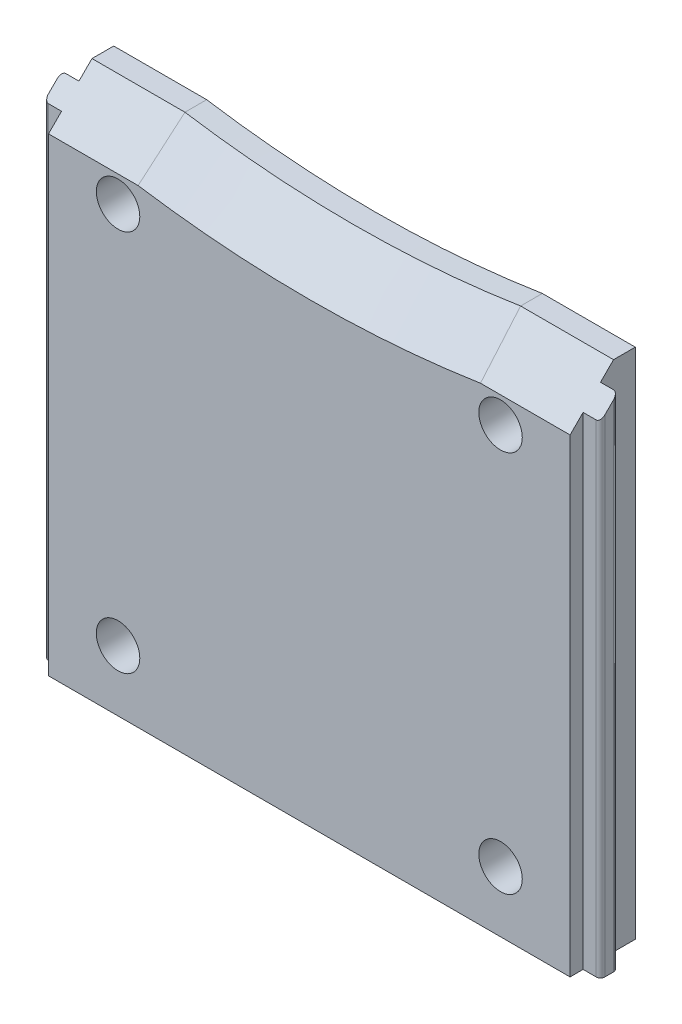
SolidWorks part; units mm, degrees
ref_plane "Front Plane" through (0, 0, 0) normal (0, 0, 1) x (1, 0, 0)
ref_plane "Top Plane" through (0, 0, 0) normal (0, 1, 0) x (1, 0, 0)
ref_plane "Right Plane" through (0, 0, 0) normal (1, 0, 0) x (0, 0, -1)
sketch "Sketch1" plane through (0, 0, 0) normal (0, 0, 1) x (1, 0, 0)
  line L0 (-15.24, 15.875) -> (-17.78, 15.875) construction
  line L1 (15.24, -15.875) -> (-15.24, -15.875)
  line L2 (15.24, -15.875) -> (15.24, 15.875) construction
  line L4 (-15.24, -15.875) -> (-15.24, 15.875) construction
  line L5 (15.24, -15.875) -> (-15.24, 15.875) construction
  line L6 (15.24, 15.875) -> (-15.24, -15.875) construction
  line L7 (15.24, 15.875) -> (17.78, 15.875) construction
  line L8 (-15.24, 15.1909) -> (-15.24, -15.875)
  line L9 (15.24, 15.1909) -> (15.24, -15.875)
  arc A1 (-17.78, 15.875) -> (17.78, 15.875) centre (0, 76.835) ccw construction
  arc A2 (-15.24, 15.1909) -> (15.24, 15.1909) centre (0, 76.835) ccw
  point P0 (0, 0)
  point P8 (0, 13.335)
  dimension "D2" = 2.54
  dimension "D1" = 31.75
  dimension "D3" = 2.54
  dimension "D4" = 30.48
extrude "Boss-Extrude1" add sketch "Sketch1" along normal blind 3.81
sketch "Sketch3" plane through (0, 0, 3.81) normal (0, 0, 1) x (1, 0, 0)
  line L1 (11.176, -12.319) -> (-11.176, -12.319) construction
  line L2 (11.176, -12.319) -> (11.176, 10.033) construction
  line L3 (11.176, 10.033) -> (-11.176, 10.033) construction
  line L4 (-11.176, -12.319) -> (-11.176, 10.033) construction
  line L5 (11.176, -12.319) -> (-11.176, 10.033) construction
  line L6 (11.176, 10.033) -> (-11.176, -12.319) construction
  circle A0 centre (-11.176, 10.033) radius 1.27
  circle A1 centre (11.176, 10.033) radius 1.27
  circle A2 centre (11.176, -12.319) radius 1.27
  circle A3 centre (-11.176, -12.319) radius 1.27
  point P0 (0, -1.143)
  dimension "D3" = 2.54
  dimension "D1" = 22.352
  dimension "D2" = 5.842
extrude "Cut-Extrude1" cut sketch "Sketch3" against normal blind 3.81
sketch "Sketch4" plane through (-15.24, 0, 0) normal (-1, 0, 0) x (0, 0, 1)
  line L0 (3.81, 15.1909) -> (0, 15.1909) construction
  line L1 (2.032, 15.1909) -> (3.048, 15.1909)
  line L2 (2.032, 15.1909) -> (2.032, -15.875)
  line L3 (2.032, -15.875) -> (3.048, -15.875)
  line L4 (3.048, 15.1909) -> (3.048, -15.875)
  line L5 (3.81, -15.875) -> (0, -15.875) construction
  line L6 (3.81, 15.1909) -> (3.81, -15.875) construction
  dimension "D1" = 1.016
  dimension "D2" = 0.762
extrude "Boss-Extrude3" add sketch "Sketch4" along normal blind 1.016
fillet "Fillet2" radius 0.254 2 edges at (-16.256, -0.342, 3.048) (-16.256, -0.342, 2.032)
mirror "Mirror4" about plane through (0, 0, 0) normal (1, 0, 0) of "Boss-Extrude3"
fillet "Fillet3" radius 0.254 2 edges at (16.256, -0.342, 3.048) (16.256, -0.342, 2.032)
sketch "Sketch5" plane through (0, 0, 3.81) normal (0, 0, 1) x (1, 0, 0)
  line L0 (15.24, 15.875) -> (17.78, 15.875) construction
  line L1 (-17.78, 15.875) -> (17.4708, 15.875)
  line L2 (-17.78, 15.875) -> (-17.78, 14.097)
  line L3 (-17.78, 14.097) -> (17.4708, 14.097)
  line L4 (17.4708, 15.875) -> (17.4708, 14.097)
  dimension "D1" = 1.778
extrude "Cut-Extrude2" cut sketch "Sketch5" against normal blind 3.81
chamfer "Chamfer1" distance 2.54 angle 45 3 edges at (12.5239, 14.097, 3.81) (-12.5239, 14.097, 3.81) (0, 13.335, 3.81)
